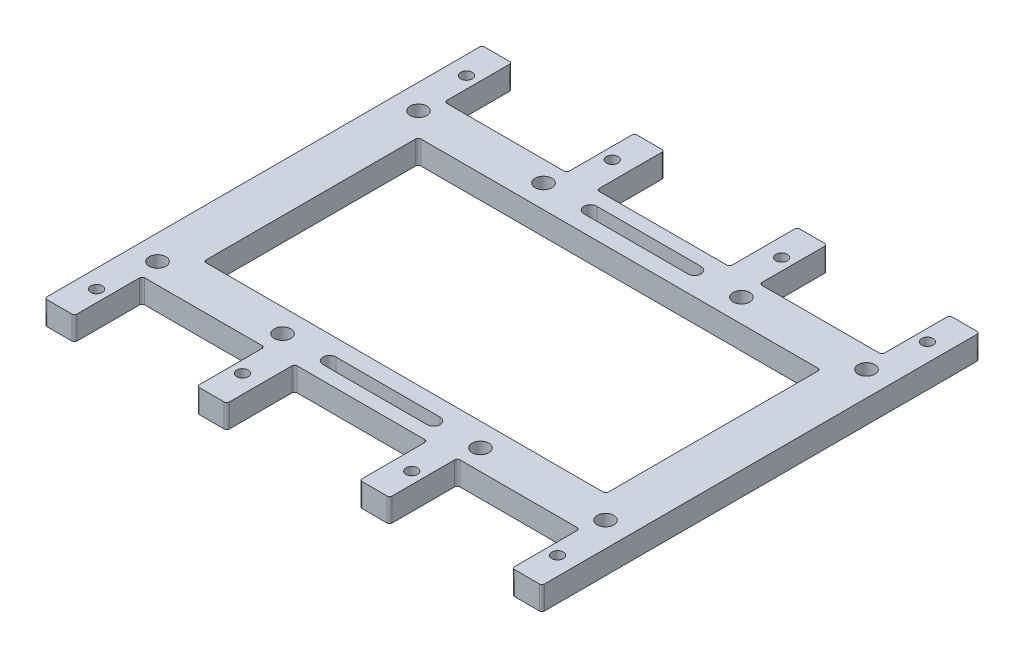
SolidWorks part; units mm, degrees
ref_plane "前视基准面" through (0, 0, 0) normal (0, 0, 1) x (1, 0, 0)
ref_plane "上视基准面" through (0, 0, 0) normal (0, 1, 0) x (1, 0, 0)
ref_plane "右视基准面" through (0, 0, 0) normal (1, 0, 0) x (0, 0, -1)
other "Configuration Table"
sketch "草图1" plane through (0, 0, 0) normal (0, 1, 0) x (1, 0, 0)
  line L0 (-47.75, -29) -> (-47.75, -42)
  line L2 (-47.75, 29) -> (-47.75, -29)
  line L4 (47.75, 29) -> (47.75, -29)
  line L5 (-47.75, 29) -> (47.75, -29) construction
  line L6 (-47.75, -29) -> (47.75, 29) construction
  line L15 (-78.7463, 0) -> (58.6748, 0) construction
  line L50 (-47.75, -42) -> (-42, -42)
  line L53 (-42, -42) -> (-42, -29)
  line L54 (-42, -29) -> (-18.5, -29)
  line L55 (-18.5, -29) -> (-18.5, -42)
  line L56 (-18.5, -42) -> (-12.75, -42)
  line L57 (-12.75, -42) -> (-12.75, -29)
  line L58 (-12.75, -29) -> (12.75, -29)
  line L59 (0, -1000) -> (0, 49000) construction
  line L60 (12.75, -42) -> (12.75, -29)
  line L61 (18.5, -42) -> (12.75, -42)
  line L62 (18.5, -29) -> (18.5, -42)
  line L63 (42, -29) -> (18.5, -29)
  line L64 (42, -42) -> (42, -29)
  line L65 (47.75, -42) -> (42, -42)
  line L66 (47.75, -29) -> (47.75, -42)
  line L67 (42, 29) -> (18.5, 29)
  line L68 (-12.75, 29) -> (12.75, 29)
  line L69 (-42, 29) -> (-18.5, 29)
  line L70 (0, 1000) -> (0, -49000) construction
  line L71 (47.75, 29) -> (47.75, 42)
  line L72 (47.75, 42) -> (42, 42)
  line L73 (42, 42) -> (42, 29)
  line L74 (18.5, 29) -> (18.5, 42)
  line L75 (18.5, 42) -> (12.75, 42)
  line L76 (12.75, 42) -> (12.75, 29)
  line L77 (-12.75, 42) -> (-12.75, 29)
  line L78 (-18.5, 42) -> (-12.75, 42)
  line L79 (-18.5, 29) -> (-18.5, 42)
  line L80 (-42, 42) -> (-42, 29)
  line L81 (-47.75, 42) -> (-42, 42)
  line L82 (-47.75, 29) -> (-47.75, 42)
  point P0 (0, 0)
  point P19 (0, -29)
  dimension "D8" = 23.5
  dimension "D10" = 12.75
  dimension "D1" = 95.5
  dimension "D2" = 58
  dimension "D3" = 13
  dimension "D4" = 13
  dimension "D5" = 13
  dimension "D6" = 13
  dimension "D7" = 5.75
  dimension "D9" = 5.75
extrude "凸台-拉伸1" add sketch "草图1" against normal blind 4.5
sketch "草图10" plane through (0, 0, 0) normal (0, 1, 0) x (1, 0, 0)
  line L5 (38.6, 20.6) -> (-38.6, 20.6)
  line L6 (38.6, 20.6) -> (38.6, -20.6)
  line L7 (38.6, -20.6) -> (-38.6, -20.6)
  line L8 (-38.6, 20.6) -> (-38.6, -20.6)
  line L9 (38.6, 20.6) -> (-38.6, -20.6) construction
  line L10 (38.6, -20.6) -> (-38.6, 20.6) construction
  point P0 (0, 0)
  dimension "D1" = 77.2
  dimension "D2" = 41.2
extrude "切除-拉伸5" cut sketch "草图10" against normal through all
sketch "草图16" plane through (0, 0, 0) normal (0, 1, 0) x (1, 0, 0)
  line L0 (-10, 25.05) -> (10, 25.05) construction
  line L1 (-10, 26.3) -> (10, 26.3)
  line L2 (-10, 23.8) -> (10, 23.8)
  line L3 (-1000, 0) -> (49000, 0) construction
  line L4 (0, -1000) -> (0, 49000) construction
  line L6 (-10, -25.05) -> (10, -25.05) construction
  line L7 (-10, -26.3) -> (10, -26.3)
  line L8 (-10, -23.8) -> (10, -23.8)
  arc A0 (-10, 26.3) -> (-10, 23.8) centre (-10, 25.05) ccw
  arc A1 (10, 23.8) -> (10, 26.3) centre (10, 25.05) ccw
  arc A2 (-10, -26.3) -> (-10, -23.8) centre (-10, -25.05) cw
  arc A3 (10, -23.8) -> (10, -26.3) centre (10, -25.05) cw
  circle A4 centre (19, 25.05) radius 1.6
  circle A5 centre (43, 25.05) radius 1.6
  circle A6 centre (-43, 25.05) radius 1.6
  circle A7 centre (-19, 25.05) radius 1.6
  circle A8 centre (43, -25.05) radius 1.6
  circle A9 centre (19, -25.05) radius 1.6
  circle A10 centre (-19, -25.05) radius 1.6
  circle A11 centre (-43, -25.05) radius 1.6
  point P2 (0, 25.05)
  point P17 (0, -25.05)
  dimension "D4" = 3.2
  dimension "D5" = 3.2
  dimension "D1" = 2.5
  dimension "D2" = 20
  dimension "D7" = 9
  dimension "D8" = 24
extrude "切除-拉伸6" cut sketch "草图16" against normal blind 10
sketch "草图17" plane through (0, 0, 0) normal (0, 1, 0) x (1, 0, 0)
  line L0 (-42, -29) -> (-18.5, -29) construction
  line L1 (-42, -42) -> (-42, -29) construction
  line L2 (-18.5, -29) -> (-18.5, -42) construction
  line L3 (-1000, 0) -> (49000, 0) construction
  line L4 (0, -1000) -> (0, 49000) construction
  circle A0 centre (-44.25, -35.5) radius 1.1
  circle A1 centre (-16.25, -35.5) radius 1.1
  circle A2 centre (16.25, -35.5) radius 1.1
  circle A3 centre (44.25, -35.5) radius 1.1
  circle A4 centre (44.25, 35.5) radius 1.1
  circle A5 centre (-16.25, 35.5) radius 1.1
  circle A6 centre (-44.25, 35.5) radius 1.1
  circle A7 centre (16.25, 35.5) radius 1.1
  point P21 (16.25, 35.5)
  dimension "D3" = 2.2
  dimension "D4" = 2.2
  dimension "D1" = 6.5
  dimension "D2" = 2.25
  dimension "D5" = 6.5
  dimension "D6" = 2.25
extrude "切除-拉伸7" cut sketch "草图17" against normal blind 10
fillet "圆角1" radius 0.5 32 edges at (42, -2.25, -29) (18.5, -2.25, -29) (12.75, -2.25, -29) (-12.75, -2.25, -29) (-18.5, -2.25, -29) (-42, -2.25, -29) (-42, -2.25, 42) (-42, -2.25, 29) (-18.5, -2.25, 29) (-18.5, -2.25, 42) (-12.75, -2.25, 42) (-12.75, -2.25, 29) (12.75, -2.25, 29) (12.75, -2.25, 42) (18.5, -2.25, 42) (18.5, -2.25, 29) (42, -2.25, 29) (42, -2.25, 42) (47.75, -2.25, 42) (-38.6, -2.25, -20.6) (38.6, -2.25, -20.6) (38.6, -2.25, 20.6) (-38.6, -2.25, 20.6) (-47.75, -2.25, 42) (47.75, -2.25, -42) (42, -2.25, -42) (18.5, -2.25, -42) (12.75, -2.25, -42) (-12.75, -2.25, -42) (-18.5, -2.25, -42) (-42, -2.25, -42) (-47.75, -2.25, -42)
sketch "草图14" plane through (0, -3, 0) normal (0, -1, 0) x (1, 0, 0)
  line L0 (4.73, 0) -> (-4.73, 0) construction
  line L1 (-42, 24) -> (-37, 24)
  line L2 (-42, 24) -> (-42, 20)
  line L3 (-42, 20) -> (-37, 20)
  line L4 (-37, 24) -> (-37, 20)
  line L5 (-42, 24) -> (-37, 20) construction
  line L6 (-42, 20) -> (-37, 24) construction
  line L7 (-42, -20) -> (-37, -20)
  line L8 (-37, -24) -> (-37, -20)
  line L9 (-42, -24) -> (-37, -24)
  line L10 (-42, -24) -> (-42, -20)
  line L11 (0, -4.73) -> (0, 4.73) construction
  line L12 (42, -24) -> (42, -20)
  line L13 (42, -24) -> (37, -24)
  line L14 (37, -24) -> (37, -20)
  line L15 (42, -20) -> (37, -20)
  line L16 (42, 20) -> (37, 20)
  line L17 (37, 24) -> (37, 20)
  line L18 (42, 24) -> (37, 24)
  line L19 (42, 24) -> (42, 20)
  point P0 (-39.5, 22)
  dimension "D1" = 22
  dimension "D2" = 5
  dimension "D3" = 4
sketch "草图15" plane through (0, -3, 0) normal (0, -1, 0) x (1, 0, 0)
  line L0 (-45, 23) -> (32, 23) construction
  line L1 (-41, 20) -> (41, 20)
  line L2 (-41, 20) -> (-41, 16)
  line L3 (-41, 16) -> (41, 16)
  line L4 (41, 20) -> (41, 16)
  line L5 (-41, 20) -> (41, 16) construction
  line L6 (-41, 16) -> (41, 20) construction
  line L7 (4.73, 0) -> (-4.73, 0) construction
  line L8 (-41, -16) -> (41, -16)
  line L9 (41, -20) -> (41, -16)
  line L10 (-41, -20) -> (41, -20)
  line L11 (-41, -20) -> (-41, -16)
  line L12 (0, -4.73) -> (0, 4.73) construction
  line L13 (-40.75, 10) -> (-38.25, 10)
  line L14 (-40.75, 10) -> (-40.75, -10)
  line L15 (-40.75, -10) -> (-38.25, -10)
  line L16 (-38.25, 10) -> (-38.25, -10)
  line L17 (-40.75, 10) -> (-38.25, -10) construction
  line L18 (-40.75, -10) -> (-38.25, 10) construction
  line L19 (40.75, -10) -> (38.25, -10)
  line L20 (38.25, 10) -> (38.25, -10)
  line L21 (40.75, 10) -> (38.25, 10)
  line L22 (40.75, 10) -> (40.75, -10)
  point P0 (0, 18)
  point P5 (-39.5, 0)
  dimension "D1" = 4
  dimension "D2" = 5
  dimension "D3" = 82
  dimension "D4" = 2.5
  dimension "D5" = 20
